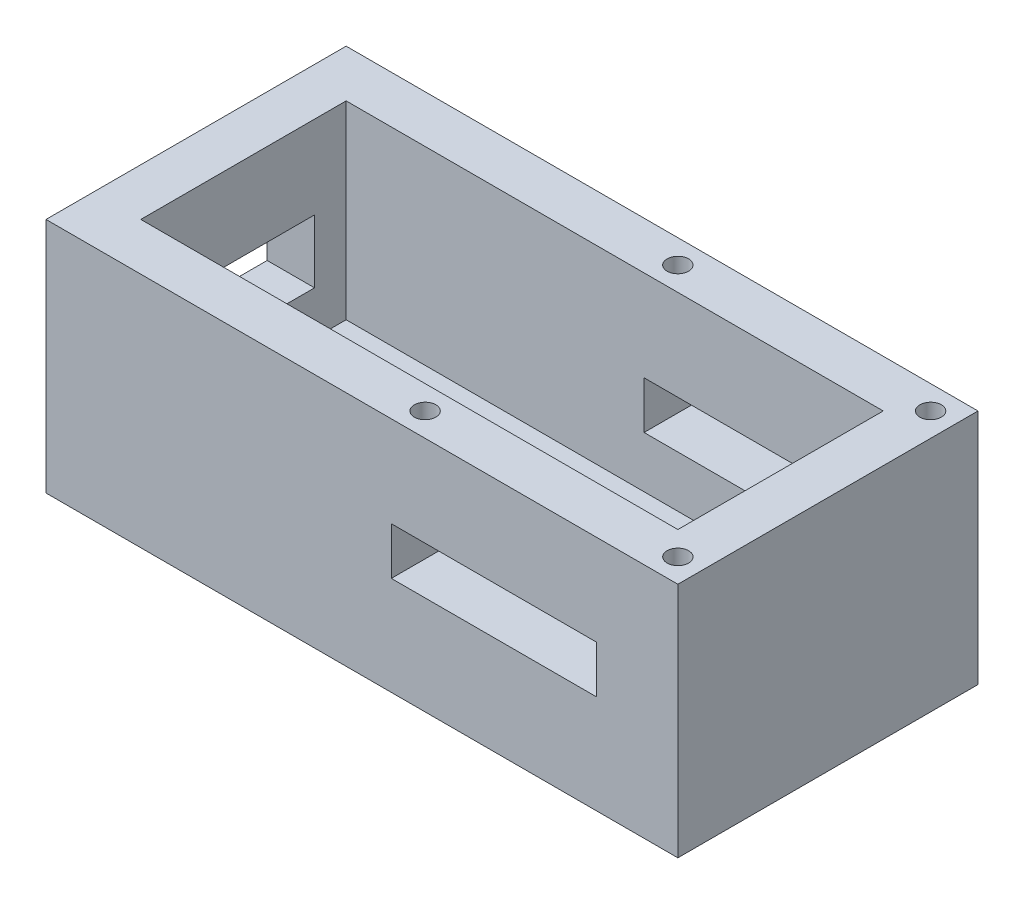
SolidWorks part; units mm, degrees
ref_plane "Front Plane" through (0, 0, 0) normal (0, 0, 1) x (1, 0, 0)
ref_plane "Top Plane" through (0, 0, 0) normal (0, 1, 0) x (1, 0, 0)
ref_plane "Right Plane" through (0, 0, 0) normal (1, 0, 0) x (0, 0, -1)
sketch "Sketch1" plane through (0, 0, 0) normal (0, 1, 0) x (1, 0, 0)
  line L1 (-50.8, -24.13) -> (50.8, -24.13)
  line L2 (-50.8, -24.13) -> (-50.8, 24.13)
  line L3 (-50.8, 24.13) -> (50.8, 24.13)
  line L4 (50.8, -24.13) -> (50.8, 24.13)
  line L5 (-50.8, -24.13) -> (50.8, 24.13) construction
  line L6 (-50.8, 24.13) -> (50.8, -24.13) construction
  point P0 (0, 0)
  dimension "D1" = 48.26
  dimension "D2" = 101.6
extrude "Boss-Extrude1" add sketch "Sketch1" along normal blind 38.1
shell "Shell1" thickness 7.62
sketch "Sketch2" plane through (0, 38.1, 0) normal (0, 1, 0) x (1, 0, 0)
  line L0 (-51.5316, 0) -> (55.8097, 0) construction
  line L1 (0, 32.6653) -> (0, -34.8642) construction
  line L3 (50.8, -24.13) -> (50.8, 24.13) construction
  line L6 (6.35, -20.32) -> (46.99, -20.32) construction
  line L7 (6.35, -20.32) -> (6.35, 20.32) construction
  line L8 (6.35, 20.32) -> (46.99, 20.32) construction
  line L9 (46.99, -20.32) -> (46.99, 20.32) construction
  line L10 (6.35, -20.32) -> (46.99, 20.32) construction
  line L11 (6.35, 20.32) -> (46.99, -20.32) construction
  circle A0 centre (6.35, 20.32) radius 1.5542
  circle A1 centre (46.99, 20.32) radius 1.5542
  circle A2 centre (46.99, -20.32) radius 1.5542
  circle A3 centre (6.35, -20.32) radius 1.5542
  point P13 (26.67, 0)
  point P14 (46.99, 20.32)
  point P15 (6.35, -20.32)
  point P16 (6.35, 20.32)
  point P17 (46.99, -20.32)
  point P27 (0, 0)
  point P28 (0, 0)
  dimension "D1" = 40.64
  dimension "D2" = 40.64
  dimension "D3" = 3.81
sketch "Sketch4" plane through (-50.8, 0, 0) normal (-1, 0, 0) x (0, 0, 1)
  line L0 (-27.572, 7.62) -> (30.9954, 7.62) construction
  line L1 (-31.0345, 19.685) -> (30.2813, 19.685) construction
  line L2 (0, 38.1) -> (0, -0.901) construction
  line L4 (-24.13, 0) -> (24.13, 0)
  line L5 (24.13, 0) -> (24.13, 38.1)
  line L6 (24.13, 38.1) -> (-24.13, 38.1)
  line L7 (-24.13, 38.1) -> (-24.13, 0)
  line L8 (-24.13, 0) -> (24.13, 0) construction
  line L9 (24.13, 0) -> (24.13, 38.1) construction
  line L10 (24.13, 38.1) -> (-24.13, 38.1) construction
  line L11 (-24.13, 38.1) -> (-24.13, 0) construction
  line L12 (-11.43, 14.605) -> (11.43, 14.605)
  line L13 (-11.43, 14.605) -> (-11.43, 24.765)
  line L14 (-11.43, 24.765) -> (11.43, 24.765)
  line L15 (11.43, 14.605) -> (11.43, 24.765)
  line L16 (-11.43, 14.605) -> (11.43, 24.765) construction
  line L17 (-11.43, 24.765) -> (11.43, 14.605) construction
  point P11 (0, 19.685)
  dimension "D2" = 7.62
  dimension "D3" = 12.065
  dimension "D4" = 10.16
  dimension "D5" = 22.86
  dimension "D1" = 0
extrude "Cut-Extrude1" cut sketch "Sketch4" against normal blind 38.1
ref_plane "Plane1" through (0, 19.685, 0) normal (0, 1, 0) x (1, 0, 0)
sketch "Sketch5" plane through (0, 0, -24.13) normal (0, 0, -1) x (-1, 0, 0)
  line L0 (-60.1777, 19.685) -> (55.1285, 19.685) construction
  line L1 (20.4258, 19.685) -> (-20.4258, 19.685) construction
  line L3 (-4.7243, 15.875) -> (-37.7443, 15.875)
  line L4 (-4.7243, 15.875) -> (-4.7243, 23.495)
  line L5 (-4.7243, 23.495) -> (-37.7443, 23.495)
  line L6 (-37.7443, 15.875) -> (-37.7443, 23.495)
  line L7 (-4.7243, 15.875) -> (-37.7443, 23.495) construction
  line L8 (-4.7243, 23.495) -> (-37.7443, 15.875) construction
  point P4 (-21.2343, 19.685)
  dimension "D1" = 7.62
  dimension "D2" = 33.02
extrude "Cut-Extrude2" cut sketch "Sketch5" against normal through all
hole_wizard "#8-32 Tapped Hole1" positions "Sketch2" profile "Sketch7" tap size "#8-32" standard "ANSI Inch"
sketch "Sketch7" plane through (46.99, 38.1, 20.32) normal (1, 0, 0) x (0, 0, 1)
  line L0 (0, 0) -> (0, 13.1028)
  line L1 (0, 13.1028) -> (1.7272, 12.065)
  line L2 (1.7272, 12.065) -> (1.7272, 0)
  line L5 (1.7272, 0) -> (0, 0)
  line L10 (0, 13.1028) -> (-1.7272, 12.065) construction
  line L11 (0, -6.35) -> (0, 107.95) construction
  dimension "Tap Drill Dia." = 3.4544
  dimension "Tap Drill Depth" = 12.065
  dimension "Drill Angle" = 118
cosmetic thread "Hole Thread13" parameters "D1"=8.382, "D2"=4.4196
cosmetic thread "Hole Thread14" parameters "D1"=8.382, "D2"=4.4196
cosmetic thread "Hole Thread15" parameters "D1"=8.382, "D2"=4.4196
cosmetic thread "Hole Thread16" parameters "D1"=8.382, "D2"=4.4196
